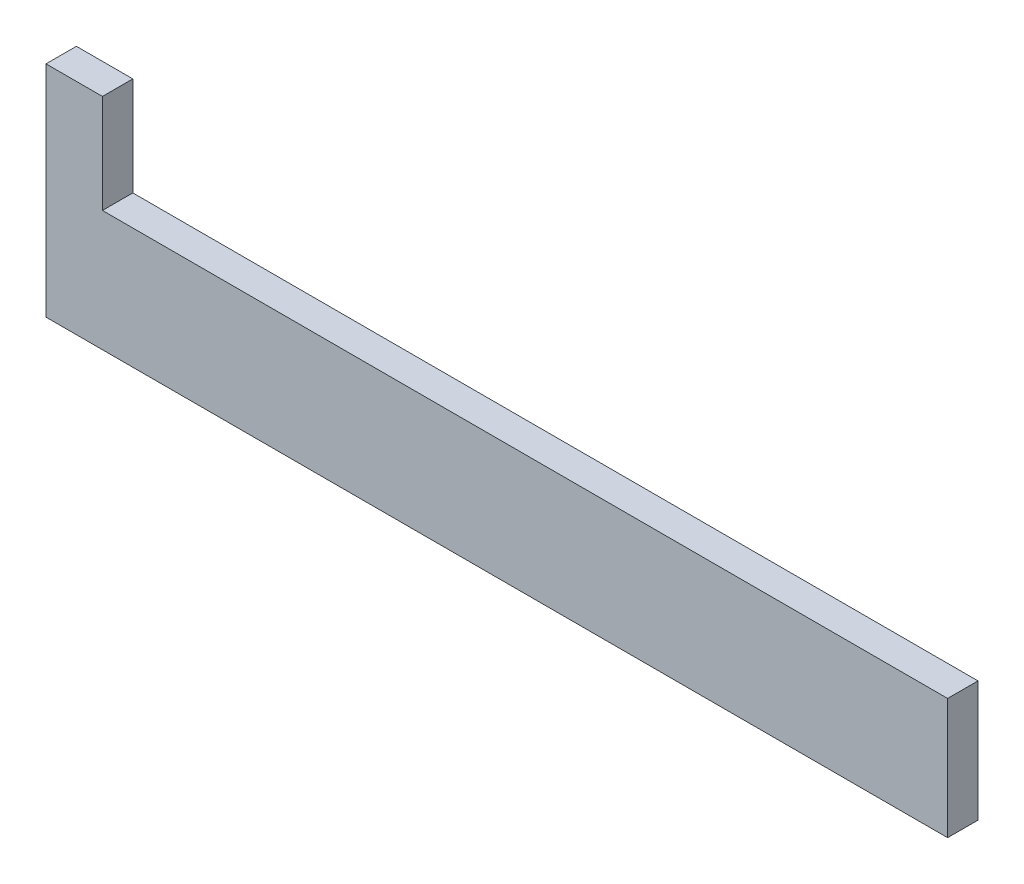
SolidWorks part; units mm, degrees
ref_plane "Front Plane" through (0, 0, 0) normal (0, 0, 1) x (1, 0, 0)
ref_plane "Top Plane" through (0, 0, 0) normal (0, 1, 0) x (1, 0, 0)
ref_plane "Right Plane" through (0, 0, 0) normal (1, 0, 0) x (0, 0, -1)
sketch "Sketch1" plane through (0, 0, 0) normal (0, 0, 1) x (1, 0, 0)
  line L0 (0, 0) -> (0, 13.0856) construction
  line L1 (28, 0) -> (-28, 0)
  line L2 (-28, 0) -> (-28, 15.549)
  line L3 (24, 8.549) -> (-24, 8.549)
  line L4 (-28, 15.549) -> (-24, 15.549)
  line L5 (-24, 15.549) -> (-24, 8.549)
  line L6 (24, 15.549) -> (24, 8.549)
  line L7 (28, 15.549) -> (24, 15.549)
  line L8 (28, 0) -> (28, 15.549)
  point P11 (0, 8.549)
  dimension "D1" = 28
  dimension "D2" = 8.549
  dimension "D3" = 4
  dimension "D4" = 7
extrude "Boss-Extrude1" add sketch "Sketch1" along normal blind 2.1537
sketch "Sketch3" plane through (24, 0, 0) normal (-1, 0, 0) x (0, 0, 1)
  line L1 (2.1537, 8.549) -> (0, 8.549)
  line L2 (2.1537, 8.549) -> (2.1537, 15.549)
  line L3 (2.1537, 15.549) -> (0, 15.549)
  line L4 (0, 8.549) -> (0, 15.549)
extrude "Cut-Extrude1" cut sketch "Sketch3" against normal up to next
sketch "Sketch4" plane through (28, 0, 0) normal (1, 0, 0) x (0, 0, -1)
  line L1 (0, 8.549) -> (-2.1537, 8.549)
  line L2 (0, 8.549) -> (0, 0)
  line L3 (0, 0) -> (-2.1537, 0)
  line L4 (-2.1537, 8.549) -> (-2.1537, 0)
extrude "Boss-Extrude2" add sketch "Sketch4" along normal blind 7.9
